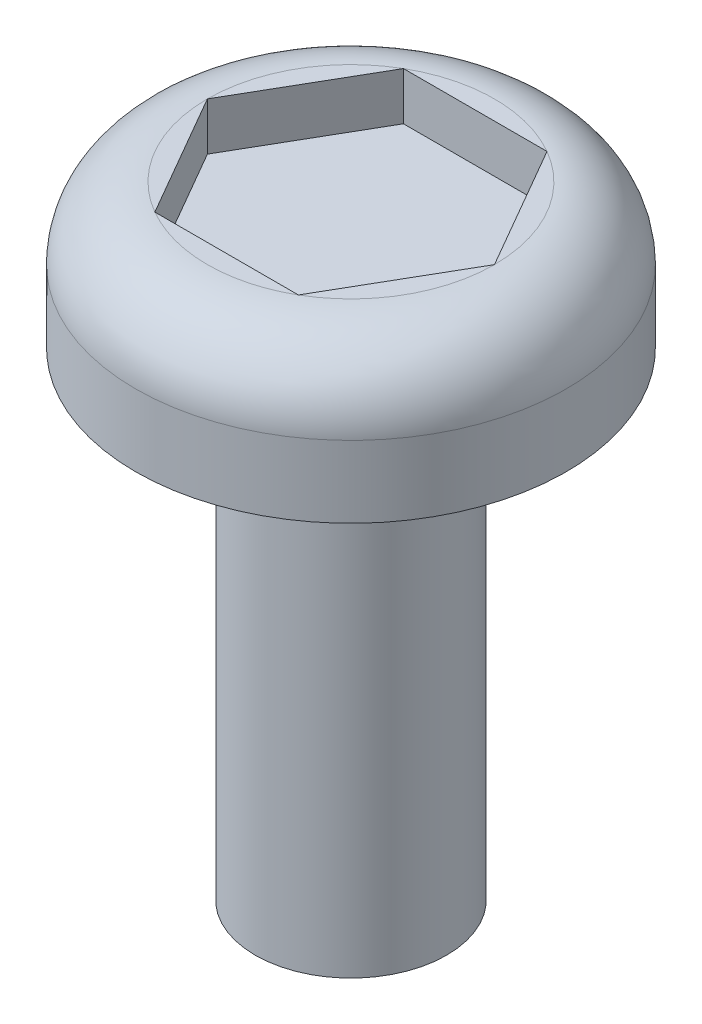
SolidWorks part; units mm, degrees
ref_plane "Front" through (0, 0, 0) normal (0, 0, 1) x (1, 0, 0)
ref_plane "Top" through (0, 0, 0) normal (0, 1, 0) x (1, 0, 0)
ref_plane "Right" through (0, 0, 0) normal (1, 0, 0) x (0, 0, -1)
sketch "Sketch1" plane through (0, 0, 0) normal (0, 1, 0) x (1, 0, 0)
  circle A0 centre (0, 0) radius 1
  dimension "D1" = 2
extrude "Boss-Extrude1" add sketch "Sketch1" along normal blind 5
sketch "Sketch2" plane through (0, 5, 0) normal (0, 1, 0) x (1, 0, 0)
  circle A0 centre (0, 0) radius 2.25
  dimension "D1" = 4.5
extrude "Boss-Extrude2" add sketch "Sketch2" along normal blind 1.5
fillet "Fillet1" radius 0.75 1 edges at (0, 6.5, 2.25)
sketch "Sketch3" plane through (0, 6.5, 0) normal (0, 1, 0) x (1, 0, 0)
  line L1 (1.5, 0) -> (0.75, 1.299)
  line L2 (0.75, 1.299) -> (-0.75, 1.299)
  line L3 (-0.75, 1.299) -> (-1.5, 0)
  line L4 (-1.5, 0) -> (-0.75, -1.299)
  line L5 (-0.75, -1.299) -> (0.75, -1.299)
  line L6 (0.75, -1.299) -> (1.5, 0)
  circle A0 centre (0, 0) radius 1.299 construction
  circle A1 centre (0, 0) radius 1.5 construction
  point P1 (1, 0)
  point P12 (0, 0)
extrude "Cut-Extrude1" cut sketch "Sketch3" against normal blind 0.5
